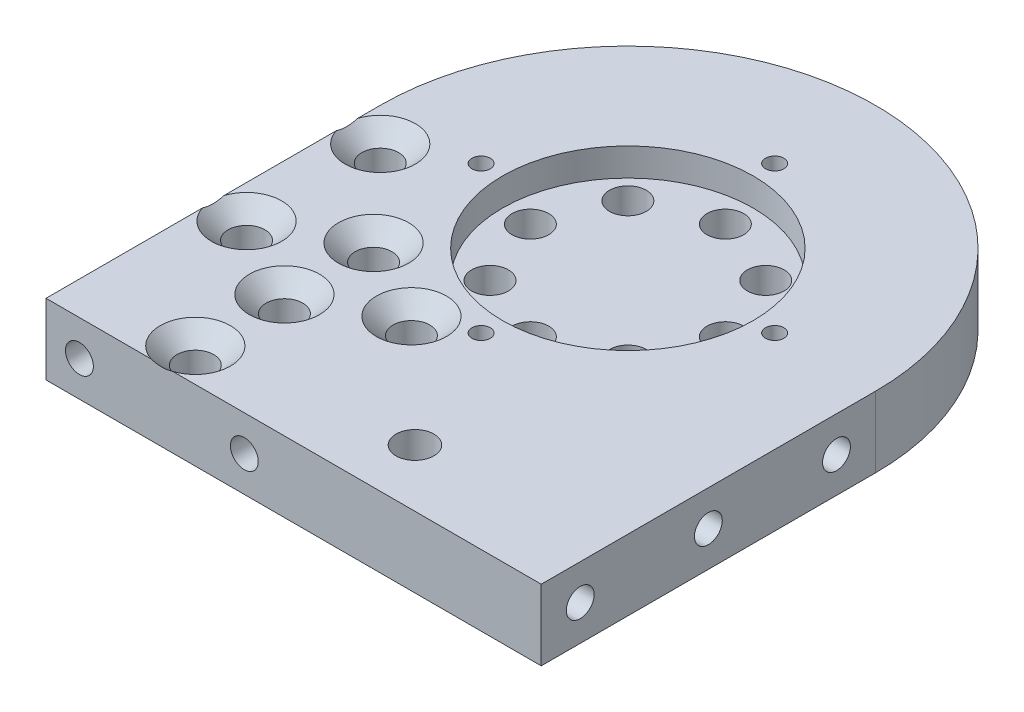
SolidWorks part; units mm, degrees
material "1060 合金"
ref_plane "前视基准面" through (0, 0, 0) normal (0, 0, 1) x (1, 0, 0)
ref_plane "上视基准面" through (0, 0, 0) normal (0, 1, 0) x (1, 0, 0)
ref_plane "右视基准面" through (0, 0, 0) normal (1, 0, 0) x (0, 0, -1)
sketch "草图1" plane through (0, 0, 0) normal (0, 1, 0) x (1, 0, 0)
  line L0 (-44.45, 0) -> (-44.45, -60)
  line L1 (-44.45, -60) -> (44.45, -60)
  line L2 (44.45, -60) -> (44.45, 0)
  arc A0 (44.45, 0) -> (-44.45, 0) centre (0, 0) ccw
  dimension "D1" = 88.9
  dimension "D2" = 60
extrude "凸台-拉伸1" add sketch "草图1" along normal blind 12.7
sketch "草图2" plane through (0, 12.7, 0) normal (0, 1, 0) x (1, 0, 0)
  circle A0 centre (0, 0) radius 22.5
  dimension "D1" = 45
extrude "切除-拉伸1" cut sketch "草图2" against normal blind 5
sketch "草图3" plane through (0, 12.7, 0) normal (0, 1, 0) x (1, 0, 0)
  circle A0 centre (0, 26.35) radius 1.65
  circle A1 centre (26.35, 0) radius 1.65
  circle A2 centre (0, -26.35) radius 1.65
  circle A3 centre (-26.35, 0) radius 1.65
  dimension "D1" = 3.3
  dimension "D2" = 26.35
  dimension "D3" = 4
extrude "切除-拉伸2" cut sketch "草图3" against normal through all
sketch "草图4" plane through (0, 7.7, 0) normal (0, 1, 0) x (1, 0, 0)
  circle A0 centre (0, 17.5) radius 3.3
  circle A1 centre (12.3744, 12.3744) radius 3.3
  circle A2 centre (17.5, 0) radius 3.3
  circle A3 centre (12.3744, -12.3744) radius 3.3
  circle A4 centre (0, -17.5) radius 3.3
  circle A5 centre (-12.3744, -12.3744) radius 3.3
  circle A6 centre (-17.5, 0) radius 3.3
  circle A7 centre (-12.3744, 12.3744) radius 3.3
  dimension "D1" = 6.6
  dimension "D2" = 17.5
  dimension "D3" = 8
extrude "切除-拉伸3" cut sketch "草图4" against normal through all
sketch "草图5" plane through (0, 12.7, 0) normal (0, 1, 0) x (1, 0, 0)
  line L0 (-44.45, 0) -> (-44.45, -60) construction
  line L1 (-44.45, -60) -> (44.45, -60) construction
  circle A0 centre (-23.65, -54) radius 3.3
  circle A1 centre (-23.65, -38) radius 3.3
  circle A2 centre (-8.85, -30) radius 3.3
  circle A3 centre (-38.45, -30) radius 3.3
  circle A4 centre (-23.65, -22) radius 3.3
  dimension "D1" = 6.6
  dimension "D2" = 20.8
  dimension "D3" = 6
  dimension "D4" = 30
  dimension "D5" = 35.6
  dimension "D6" = 20.8
  dimension "D7" = 16
  dimension "D8" = 16
  dimension "D9" = 20.8
  dimension "D10" = 6
  dimension "D11" = 30
extrude "切除-拉伸4" cut sketch "草图5" against normal through all and the other way through all
sketch "草图6" plane through (0, 12.7, 0) normal (0, 1, 0) x (1, 0, 0)
  circle A0 centre (-23.65, -22) radius 6.3
  circle A1 centre (-8.85, -30) radius 6.3
  circle A2 centre (-23.65, -38) radius 6.3
  circle A3 centre (-38.45, -30) radius 6.3
  circle A4 centre (-23.65, -54) radius 6.3
  dimension "D1" = 12.6
extrude "切除-拉伸5" cut sketch "草图6" against normal blind 3 draft 45
sketch "草图7" plane through (0, 12.7, 0) normal (0, 1, 0) x (1, 0, 0)
  line L0 (-44.45, 0) -> (-44.45, -28.0791) construction
  circle A0 centre (-38.45, -6) radius 3.3
  circle A1 centre (-38.45, -30) radius 3.3 construction
  dimension "D1" = 6.6
  dimension "D2" = 24
  dimension "D3" = 6
extrude "切除-拉伸6" cut sketch "草图7" against normal through all
sketch "草图8" plane through (0, 12.7, 0) normal (0, 1, 0) x (1, 0, 0)
  circle A0 centre (-38.45, -6) radius 6.3
  dimension "D1" = 12.6
extrude "切除-拉伸7" cut sketch "草图8" against normal blind 3 draft 45
sketch "草图9" plane through (0, 0, 60) normal (0, 0, 1) x (1, 0, 0)
  line L0 (-44.45, 12.7) -> (-44.45, 0) construction
  line L1 (-44.45, 12.7) -> (-25.5709, 12.7) construction
  line L2 (-21.7291, 12.7) -> (44.45, 12.7) construction
  circle A0 centre (-38.45, 6.35) radius 2.5
  circle A1 centre (-8.85, 6.35) radius 2.5
  dimension "D1" = 5
  dimension "D2" = 5
  dimension "D3" = 6
  dimension "D4" = 6.35
  dimension "D5" = 6.35
  dimension "D6" = 29.6
extrude "切除-拉伸8" cut sketch "草图9" against normal blind 15
sketch "草图10" plane through (0, 12.7, 0) normal (0, 1, 0) x (1, 0, 0)
  line L0 (-44.45, -31.9209) -> (-44.45, -60) construction
  line L1 (-21.7291, -60) -> (44.45, -60) construction
  circle A0 centre (11.47, -49.69) radius 3.4
  dimension "D1" = 6.8
  dimension "D2" = 55.92
  dimension "D3" = 10.31
extrude "切除-拉伸9" cut sketch "草图10" against normal through all
sketch "草图11" plane through (44.45, 0, 0) normal (1, 0, 0) x (0, 0, -1)
  line L0 (-60, 12.7) -> (0, 12.7) construction
  line L1 (-60, 12.7) -> (-60, 0) construction
  circle A0 centre (-53, 6.35) radius 2.5
  circle A1 centre (-30, 6.35) radius 2.5
  circle A2 centre (-7, 6.35) radius 2.5
  dimension "D1" = 5
  dimension "D2" = 6.35
  dimension "D3" = 7
  dimension "D4" = 3
extrude "切除-拉伸10" cut sketch "草图11" against normal blind 10
